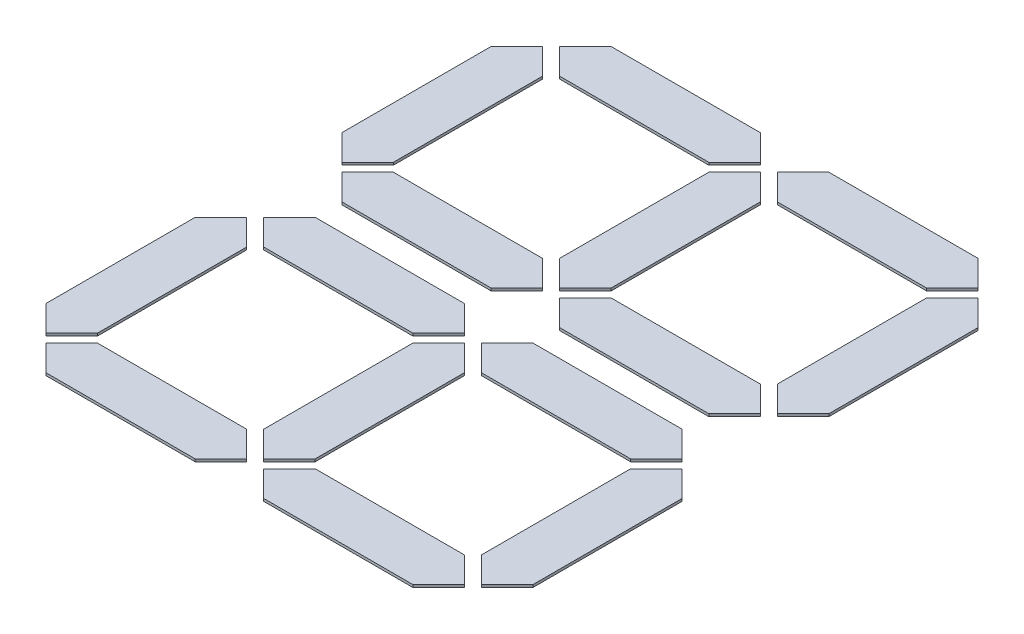
SolidWorks part; units mm, degrees
other "Camera2"
ref_plane "Front Plane" through (0, 0, 0) normal (0, 0, 1) x (1, 0, 0)
ref_plane "Top Plane" through (0, 0, 0) normal (0, 1, 0) x (1, 0, 0)
ref_plane "Right Plane" through (0, 0, 0) normal (1, 0, 0) x (0, 0, -1)
sketch "Esboço1" plane through (0, 6.8, 0) normal (0, 1, 0) x (1, 0, 0)
  line B0 (-165.1731, 288.6715) -> (-144.9231, 308.9215)
  line B1 (-185.4231, 308.9215) -> (-165.1731, 288.6715)
  line B2 (-185.4231, 426.3715) -> (-185.4231, 308.9215)
  line B3 (-165.1731, 446.6215) -> (-185.4231, 426.3715)
  line B4 (-144.9231, 426.3715) -> (-165.1731, 446.6215)
  line B5 (-144.9231, 308.9215) -> (-144.9231, 426.3715)
  line B6 (-309.6231, 261.6715) -> (-192.1731, 261.6715)
  line B7 (-329.8731, 281.9215) -> (-309.6231, 261.6715)
  line B8 (-309.6231, 302.1715) -> (-329.8731, 281.9215)
  line B9 (-192.1731, 302.1715) -> (-309.6231, 302.1715)
  line B10 (-171.9231, 281.9215) -> (-192.1731, 302.1715)
  line B11 (-192.1731, 261.6715) -> (-171.9231, 281.9215)
  line B12 (-192.1731, 473.6215) -> (-309.6231, 473.6215)
  line B13 (-171.9231, 453.3715) -> (-192.1731, 473.6215)
  line B14 (-192.1731, 433.1215) -> (-171.9231, 453.3715)
  line B15 (-309.6231, 433.1215) -> (-192.1731, 433.1215)
  line B16 (-329.8731, 453.3715) -> (-309.6231, 433.1215)
  line B17 (-309.6231, 473.6215) -> (-329.8731, 453.3715)
  line B18 (-336.6231, 446.6215) -> (-356.8731, 426.3715)
  line B19 (-316.3731, 426.3715) -> (-336.6231, 446.6215)
  line B20 (-316.3731, 308.9215) -> (-316.3731, 426.3715)
  line B21 (-336.6231, 288.6715) -> (-316.3731, 308.9215)
  line B22 (-356.8731, 308.9215) -> (-336.6231, 288.6715)
  line B23 (-356.8731, 426.3715) -> (-356.8731, 308.9215)
  line B24 (-0.4731, 453.3715) -> (-20.7231, 473.6215)
  line B25 (-20.7231, 433.1215) -> (-0.4731, 453.3715)
  line B26 (-138.1731, 433.1215) -> (-20.7231, 433.1215)
  line B27 (-158.4231, 453.3715) -> (-138.1731, 433.1215)
  line B28 (-138.1731, 473.6215) -> (-158.4231, 453.3715)
  line B29 (-20.7231, 473.6215) -> (-138.1731, 473.6215)
  line B30 (26.5269, 308.9215) -> (26.5269, 426.3715)
  line B31 (6.2769, 288.6715) -> (26.5269, 308.9215)
  line B32 (-13.9731, 308.9215) -> (6.2769, 288.6715)
  line B33 (-13.9731, 426.3715) -> (-13.9731, 308.9215)
  line B34 (6.2769, 446.6215) -> (-13.9731, 426.3715)
  line B35 (26.5269, 426.3715) -> (6.2769, 446.6215)
  line B36 (-20.7231, 261.6715) -> (-0.4731, 281.9215)
  line B37 (-138.1731, 261.6715) -> (-20.7231, 261.6715)
  line B38 (-158.4231, 281.9215) -> (-138.1731, 261.6715)
  line B39 (-138.1731, 302.1715) -> (-158.4231, 281.9215)
  line B40 (-20.7231, 302.1715) -> (-138.1731, 302.1715)
  line B41 (-0.4731, 281.9215) -> (-20.7231, 302.1715)
  line B42 (-165.1731, 55.6715) -> (-144.9231, 75.9215)
  line B43 (-185.4231, 75.9215) -> (-165.1731, 55.6715)
  line B44 (-185.4231, 193.3715) -> (-185.4231, 75.9215)
  line B45 (-165.1731, 213.6215) -> (-185.4231, 193.3715)
  line B46 (-144.9231, 193.3715) -> (-165.1731, 213.6215)
  line B47 (-144.9231, 75.9215) -> (-144.9231, 193.3715)
  line B48 (-309.6231, 28.6715) -> (-192.1731, 28.6715)
  line B49 (-329.8731, 48.9215) -> (-309.6231, 28.6715)
  line B50 (-309.6231, 69.1715) -> (-329.8731, 48.9215)
  line B51 (-192.1731, 69.1715) -> (-309.6231, 69.1715)
  line B52 (-171.9231, 48.9215) -> (-192.1731, 69.1715)
  line B53 (-192.1731, 28.6715) -> (-171.9231, 48.9215)
  line B54 (-192.1731, 240.6215) -> (-309.6231, 240.6215)
  line B55 (-171.9231, 220.3715) -> (-192.1731, 240.6215)
  line B56 (-192.1731, 200.1215) -> (-171.9231, 220.3715)
  line B57 (-309.6231, 200.1215) -> (-192.1731, 200.1215)
  line B58 (-329.8731, 220.3715) -> (-309.6231, 200.1215)
  line B59 (-309.6231, 240.6215) -> (-329.8731, 220.3715)
  line B60 (-336.6231, 213.6215) -> (-356.8731, 193.3715)
  line B61 (-316.3731, 193.3715) -> (-336.6231, 213.6215)
  line B62 (-316.3731, 75.9215) -> (-316.3731, 193.3715)
  line B63 (-336.6231, 55.6715) -> (-316.3731, 75.9215)
  line B64 (-356.8731, 75.9215) -> (-336.6231, 55.6715)
  line B65 (-356.8731, 193.3715) -> (-356.8731, 75.9215)
  line B66 (-0.4731, 220.3715) -> (-20.7231, 240.6215)
  line B67 (-20.7231, 200.1215) -> (-0.4731, 220.3715)
  line B68 (-138.1731, 200.1215) -> (-20.7231, 200.1215)
  line B69 (-158.4231, 220.3715) -> (-138.1731, 200.1215)
  line B70 (-138.1731, 240.6215) -> (-158.4231, 220.3715)
  line B71 (-20.7231, 240.6215) -> (-138.1731, 240.6215)
  line B72 (26.5269, 75.9215) -> (26.5269, 193.3715)
  line B73 (6.2769, 55.6715) -> (26.5269, 75.9215)
  line B74 (-13.9731, 75.9215) -> (6.2769, 55.6715)
  line B75 (-13.9731, 193.3715) -> (-13.9731, 75.9215)
  line B76 (6.2769, 213.6215) -> (-13.9731, 193.3715)
  line B77 (26.5269, 193.3715) -> (6.2769, 213.6215)
  line B78 (-20.7231, 28.6715) -> (-0.4731, 48.9215)
  line B79 (-138.1731, 28.6715) -> (-20.7231, 28.6715)
  line B80 (-158.4231, 48.9215) -> (-138.1731, 28.6715)
  line B81 (-138.1731, 69.1715) -> (-158.4231, 48.9215)
  line B82 (-20.7231, 69.1715) -> (-138.1731, 69.1715)
  line B83 (-0.4731, 48.9215) -> (-20.7231, 69.1715)
sketch_block_instance "Bloco1-1"
sketch_block "Bloco1"
sketch_block_instance "Bloco1-2"
extrude "Ressalto-extrusão1" add sketch "Esboço1" along normal blind 2 separate body
